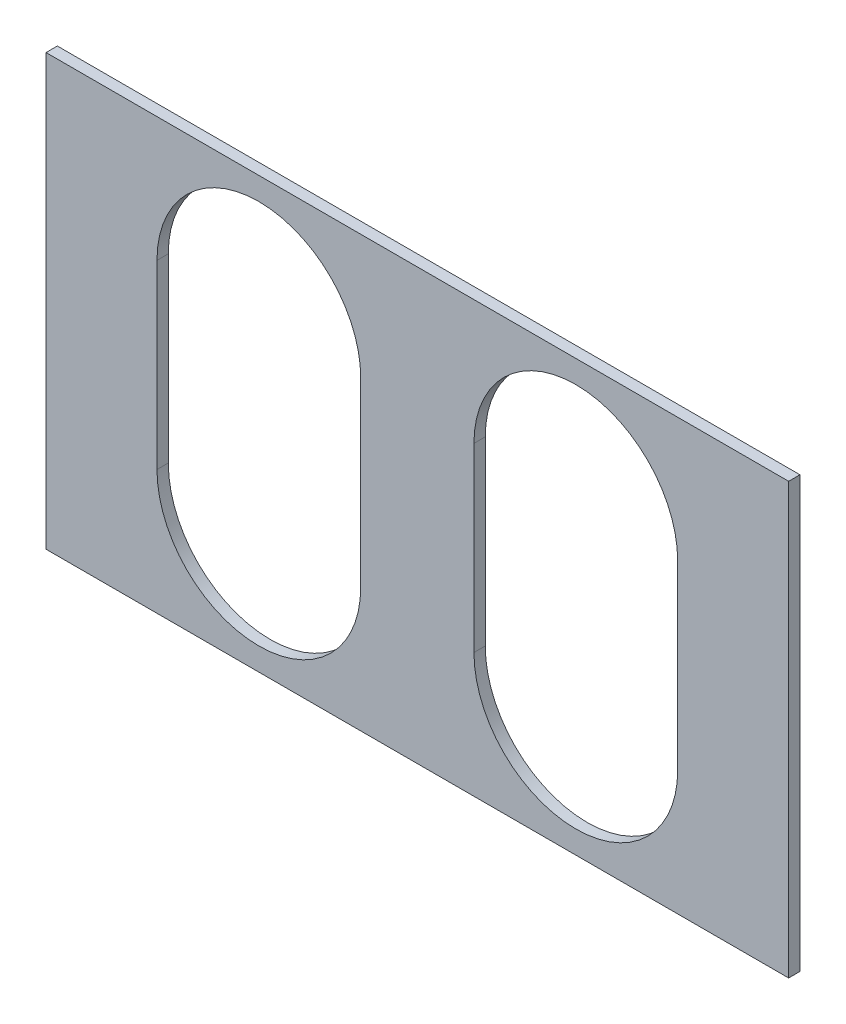
SolidWorks part; units mm, degrees
ref_plane "Спереди" through (0, 0, 0) normal (0, 0, 1) x (1, 0, 0)
ref_plane "Сверху" through (0, 0, 0) normal (0, 1, 0) x (1, 0, 0)
ref_plane "Справа" through (0, 0, 0) normal (1, 0, 0) x (0, 0, -1)
other "Configuration Table"
sketch "Эскиз1" plane through (0, 0, 0) normal (0, 0, 1) x (1, 0, 0)
  line L0 (-70, 40) -> (-70, -40) construction
  line L1 (164, 95) -> (-164, 95)
  line L2 (164, 95) -> (164, -95)
  line L3 (164, -95) -> (-164, -95)
  line L4 (-164, 95) -> (-164, -95)
  line L5 (164, 95) -> (-164, -95) construction
  line L6 (164, -95) -> (-164, 95) construction
  line L7 (-223.1783, 0) -> (249.0602, 0) construction
  line L8 (-25, 40) -> (-25, -40)
  line L9 (-115, 40) -> (-115, -40)
  line L10 (0, 83.5858) -> (0, -135.7738) construction
  line L11 (70, 40) -> (70, -40) construction
  line L12 (25, 40) -> (25, -40)
  line L13 (115, 40) -> (115, -40)
  arc A0 (-25, 40) -> (-115, 40) centre (-70, 40) ccw
  arc A1 (-115, -40) -> (-25, -40) centre (-70, -40) ccw
  arc A2 (25, 40) -> (115, 40) centre (70, 40) cw
  arc A3 (115, -40) -> (25, -40) centre (70, -40) cw
  point P0 (0, 0)
  point P10 (-70, 0)
  point P19 (70, 0)
  dimension "D1" = 190
  dimension "D2" = 328
  dimension "D3" = 90
  dimension "D4" = 170
  dimension "D5" = 25
  dimension "D6" = 164
extrude "Бобышка-Вытянуть1" add sketch "Эскиз1" along normal blind 5
sketch "Эскиз2" plane through (0, 0, 5) normal (0, 0, 1) x (1, 0, 0)
  line L8 (-25, -40) -> (-25, 40) construction
  line L9 (-25, 40) -> (25, 40)
  line L10 (-25, 40) -> (-25, -40)
  line L11 (-25, -40) -> (25, -40)
  line L12 (25, 40) -> (25, -40)
  line L13 (25, 40) -> (25, -40) construction
  point P8 (25, 0)
  dimension "D1" = 80
extrude "Бобышка-Вытянуть2" [suppressed] add sketch "Эскиз2" along normal blind 73
sketch "Эскиз3" [suppressed] plane through (-20, 0, 0) normal (-1, 0, 0) x (0, 0, 1)
  line L0 (78, 40) -> (78, -40) construction
  circle A0 centre (78, 0) radius 21.5
  dimension "D1" = 43
extrude "Вырез-Вытянуть1" [suppressed] cut sketch "Эскиз3" against normal up to surface (40 mm away)
sketch "Эскиз4" plane through (-25, 0, 0) normal (-1, 0, 0) x (0, 0, 1)
  line L1 (16.5, -22.5) -> (49.5, -22.5) construction
  line L2 (16.5, -14) -> (49.5, -14)
  line L3 (16.5, -31) -> (49.5, -31)
  line L4 (-36.3542, 0) -> (121.0228, 0) construction
  line L5 (0, 95) -> (0, -95) construction
  line L6 (16.5, 22.5) -> (49.5, 22.5) construction
  line L7 (16.5, 14) -> (49.5, 14)
  line L8 (16.5, 31) -> (49.5, 31)
  arc A3 (16.5, -14) -> (16.5, -31) centre (16.5, -22.5) ccw
  arc A4 (49.5, -31) -> (49.5, -14) centre (49.5, -22.5) ccw
  arc A5 (16.5, 14) -> (16.5, 31) centre (16.5, 22.5) cw
  arc A6 (49.5, 31) -> (49.5, 14) centre (49.5, 22.5) cw
  point P7 (33, -22.5)
  point P15 (8, -22.5)
  point P20 (33, 22.5)
  dimension "D1" = 17
  dimension "D2" = 50
  dimension "D3" = 14
  dimension "D4" = 8
extrude "Вырез-Вытянуть2" [suppressed] cut sketch "Эскиз4" against normal up to surface (40 mm away)
